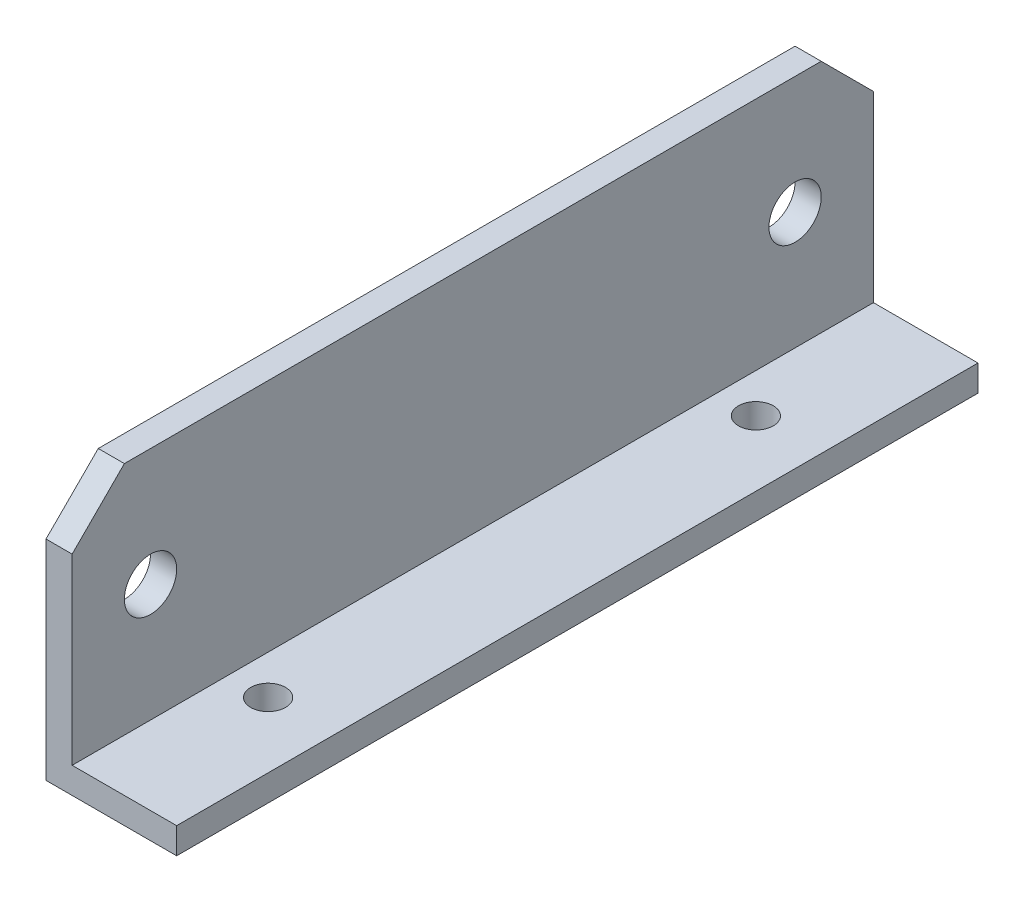
SolidWorks part; units mm, degrees
ref_plane "Front Plane" through (0, 0, 0) normal (0, 0, 1) x (1, 0, 0)
ref_plane "Top Plane" through (0, 0, 0) normal (0, 1, 0) x (1, 0, 0)
ref_plane "Right Plane" through (0, 0, 0) normal (1, 0, 0) x (0, 0, -1)
sketch "Sketch1" plane through (0, 0, 0) normal (0, 0, 1) x (1, 0, 0)
  line L0 (0, 0) -> (7.5, 0)
  line L1 (0, 0) -> (0, 15)
extrude "Extrude-Thin1" add sketch "Sketch1" along normal blind 46 thin thin type one direction wall 1.5
sketch "Sketch2" plane through (0, 1.5, 0) normal (0, 1, 0) x (1, 0, 0)
  line L0 (10, -23) -> (19.3168, -23) construction
  line L1 (3.75, -46) -> (3.75, -48.1015) construction
  circle A0 centre (3.75, -9) radius 1
  circle A1 centre (3.75, -37) radius 1
  dimension "D1" = 14
extrude "Cut-Extrude1" cut sketch "Sketch2" against normal through all
sketch "Sketch3" plane through (0, 0, 0) normal (-1, 0, 0) x (0, 0, 1)
  line L0 (23, 10) -> (23, 22.0484) construction
  line L1 (46, 0) -> (0, 0) construction
  circle A0 centre (41.5, 8.25) radius 1.5
  circle A1 centre (4.5, 8.25) radius 1.5
  dimension "D1" = 18.5
  dimension "D2" = 8.25
extrude "Cut-Extrude2" cut sketch "Sketch3" against normal through all
sketch "Sketch4" plane through (0, 0, 0) normal (-1, 0, 0) x (0, 0, 1)
  line L0 (0, 12) -> (3, 15)
  line L1 (0, 0) -> (0, 15) construction
  line L2 (46, 15) -> (0, 15) construction
  line L3 (23, 10) -> (23, 19.7932) construction
  line L4 (0, 12) -> (0, 15)
  line L5 (0, 15) -> (3, 15)
  line L6 (46, 15) -> (43, 15)
  line L7 (46, 12) -> (46, 15)
  line L8 (46, 12) -> (43, 15)
  dimension "D1" = 3
  dimension "D2" = 3
extrude "Cut-Extrude3" cut sketch "Sketch4" against normal through all
